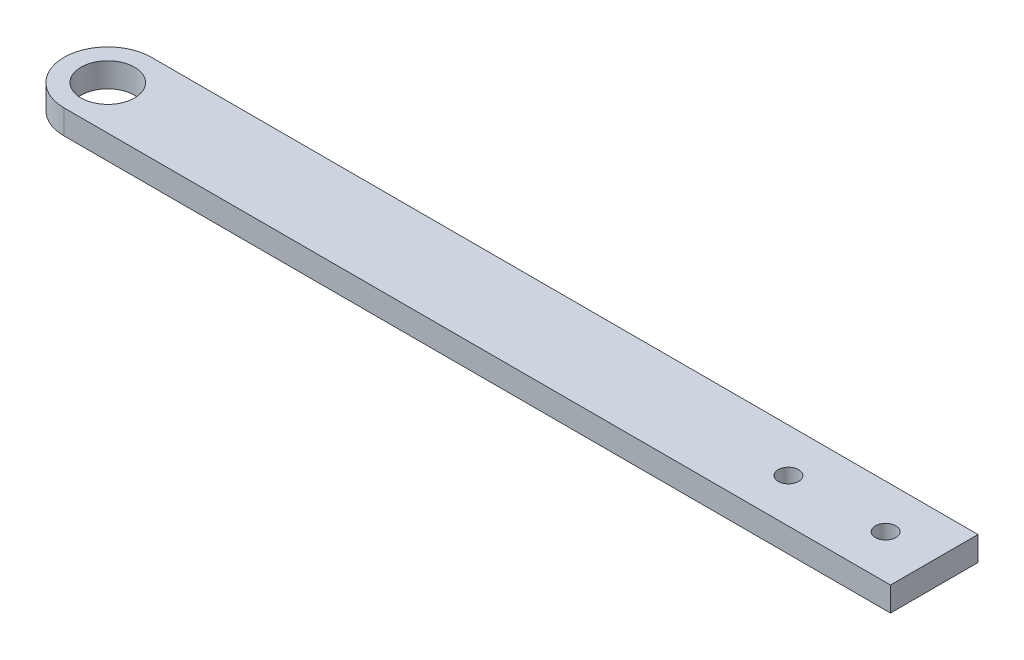
SolidWorks part; units mm, degrees
ref_plane "Front Plane" through (0, 0, 0) normal (0, 0, 1) x (1, 0, 0)
ref_plane "Top Plane" through (0, 0, 0) normal (0, 1, 0) x (1, 0, 0)
ref_plane "Right Plane" through (0, 0, 0) normal (1, 0, 0) x (0, 0, -1)
sketch "Sketch1" plane through (0, 0, 0) normal (0, 1, 0) x (1, 0, 0)
  line L0 (0, 0) -> (-170, 0)
  line L1 (-170, -18) -> (0, -18)
  line L2 (0, -18) -> (0, 0)
  arc A0 (-170, 0) -> (-170, -18) centre (-170, -9) ccw
  dimension "D1" = 9
  dimension "D2" = 170
extrude "Boss-Extrude1" add sketch "Sketch1" along normal blind 5
sketch "Sketch4" plane through (0, 5, 0) normal (0, 1, 0) x (1, 0, 0)
  line L0 (0, 0) -> (-170, 0) construction
  line L1 (0, -18) -> (0, 0) construction
  circle A0 centre (-10, -9) radius 2.1
  circle A1 centre (-30, -9) radius 2.1
  dimension "D1" = 4.2
  dimension "D2" = 9
  dimension "D3" = 10
  dimension "D4" = 20
extrude "Cut-Extrude2" cut sketch "Sketch4" against normal through all
sketch "Sketch5" plane through (0, 5, 0) normal (0, 1, 0) x (1, 0, 0)
  circle A0 centre (-170, -9) radius 5.5
  dimension "D1" = 11
extrude "Cut-Extrude3" cut sketch "Sketch5" against normal through all
